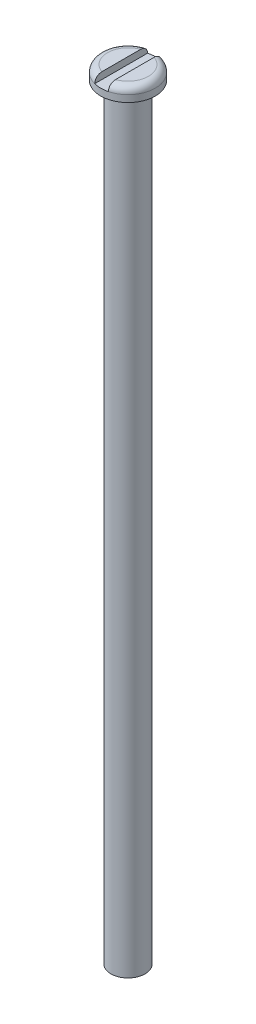
SolidWorks part; units mm, degrees
ref_plane "Front Plane" through (0, 0, 0) normal (0, 0, 1) x (1, 0, 0)
ref_plane "Top Plane" through (0, 0, 0) normal (0, 1, 0) x (1, 0, 0)
ref_plane "Right Plane" through (0, 0, 0) normal (1, 0, 0) x (0, 0, -1)
sketch "Sketch1" plane through (0, 0, 0) normal (0, 0, 1) x (1, 0, 0)
  line L0 (0, -28.5) -> (0, 28.5) construction
  line L1 (0, -28.5) -> (1.25, -28.5)
  line L2 (1.25, -28.5) -> (1.25, 27.5)
  line L3 (1.25, 27.5) -> (2, 27.5)
  line L4 (2, 27.5) -> (2, 28)
  line L5 (1.5, 28.5) -> (0, 28.5)
  line L6 (0, 28.5) -> (0, -28.5)
  arc A0 (2, 28) -> (1.5, 28.5) centre (1.5, 28) ccw
  point P4 (0, 0)
  point P11 (2, 28.5)
  dimension "D5" = 0.5
  dimension "D1" = 57
  dimension "D2" = 2.5
  dimension "D3" = 4
  dimension "D4" = 1
revolve "Revolve1" add sketch "Sketch1" angle 360 about L0
sketch "Sketch2" plane through (0, 28.5, 0) normal (0, 1, 0) x (1, 0, 0)
  line L1 (-0.5, 4) -> (0.5, 4)
  line L2 (-0.5, 4) -> (-0.5, -4)
  line L3 (-0.5, -4) -> (0.5, -4)
  line L4 (0.5, 4) -> (0.5, -4)
  line L5 (-0.5, 4) -> (0.5, -4) construction
  line L6 (-0.5, -4) -> (0.5, 4) construction
  point P0 (0, 0)
  dimension "D1" = 1
  dimension "D2" = 8
extrude "Cut-Extrude1" cut sketch "Sketch2" against normal blind 0.5
